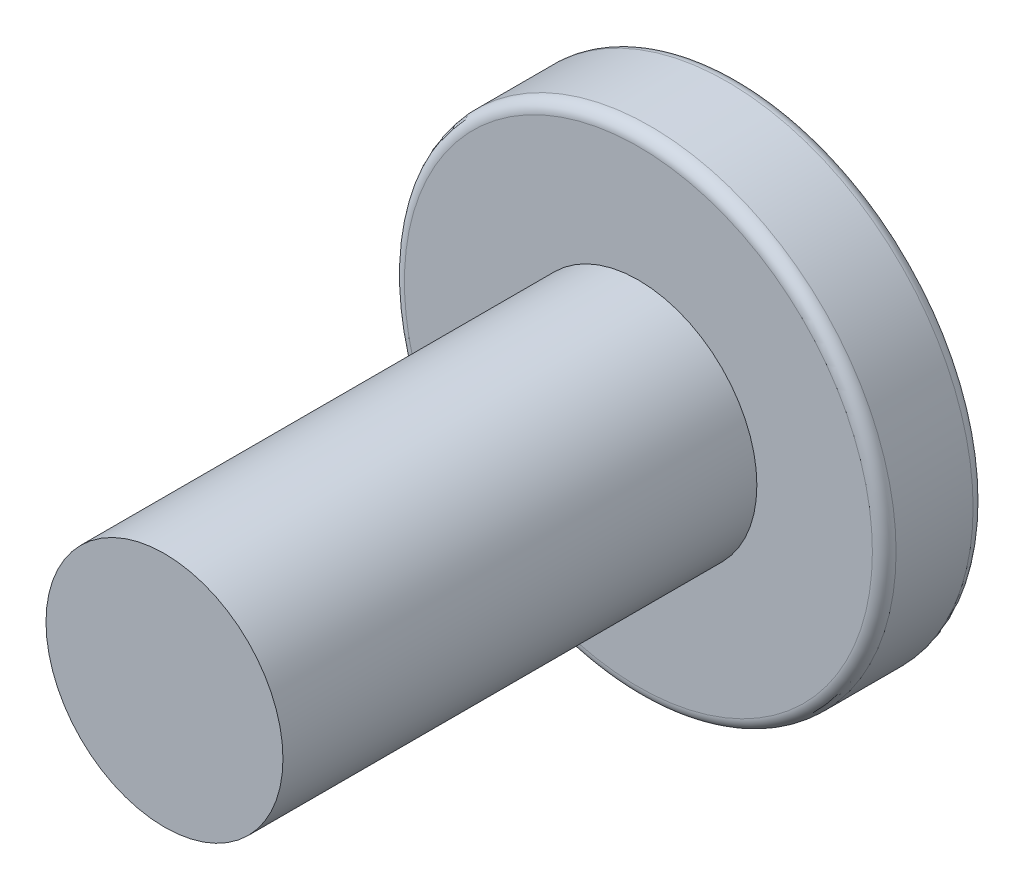
SolidWorks part; units mm, degrees
material "AISI 304"
ref_plane "前视基准面" through (0, 0, 0) normal (0, 0, 1) x (1, 0, 0)
ref_plane "上视基准面" through (0, 0, 0) normal (0, 1, 0) x (1, 0, 0)
ref_plane "右视基准面" through (0, 0, 0) normal (1, 0, 0) x (0, 0, -1)
other "Configuration Table"
sketch "草图1" plane through (0, 0, 0) normal (0, 0, 1) x (1, 0, 0)
  circle A0 centre (0, 0) radius 4.15
  dimension "D1" = 8.3
extrude "凸台-拉伸1" add sketch "草图1" along normal blind 1.7
sketch "草图2" plane through (0, 0, 1.7) normal (0, 0, 1) x (1, 0, 0)
  circle A1 centre (0, 0) radius 2
  dimension "D2" = 4
extrude "凸台-拉伸2" add sketch "草图2" along normal blind 8
fillet "圆角1" radius 0.2 2 edges at (4.15, 0, 0) (4.15, 0, 1.7)
sketch "草图3" plane through (0, 0, 0) normal (0, 0, -1) x (-1, 0, 0)
  line L0 (0, 0) -> (1.1547, 0) construction
  line L1 (1.1547, 0) -> (0.5774, 1)
  line L2 (0.5774, 1) -> (-0.5774, 1)
  line L3 (-0.5774, 1) -> (-1.1547, 0)
  line L4 (-1.1547, 0) -> (-0.5774, -1)
  line L5 (-0.5774, -1) -> (0.5774, -1)
  line L6 (0.5774, -1) -> (1.1547, 0)
  circle A0 centre (0, 0) radius 1 construction
  dimension "D1" = 2
extrude "切除-拉伸1" cut sketch "草图3" against normal blind 1.5
